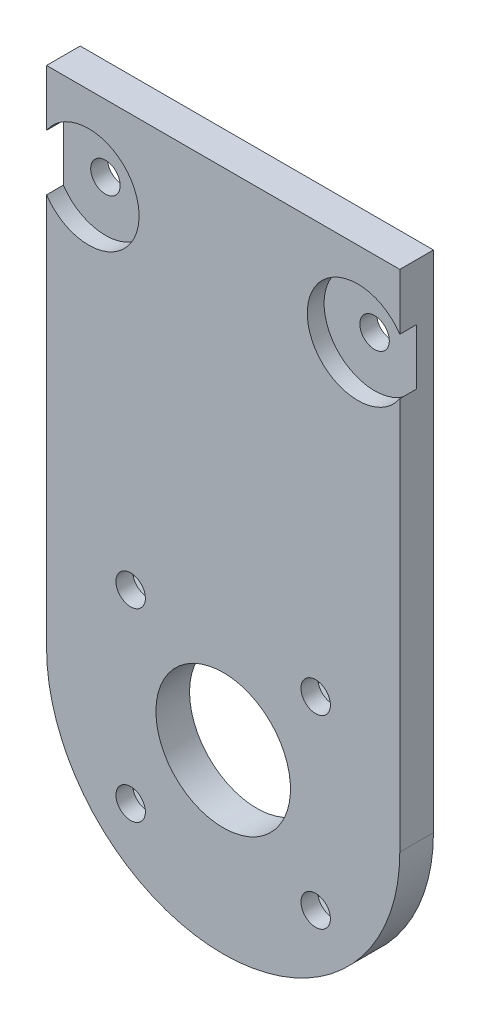
SolidWorks part; units mm, degrees
ref_plane "Front Plane" through (0, 0, 0) normal (0, 0, 1) x (1, 0, 0)
ref_plane "Top Plane" through (0, 0, 0) normal (0, 1, 0) x (1, 0, 0)
ref_plane "Right Plane" through (0, 0, 0) normal (1, 0, 0) x (0, 0, -1)
sketch "Sketch1" plane through (0, 0, 0) normal (0, 0, 1) x (1, 0, 0)
  line L2 (-21, 0) -> (-21, 60)
  line L3 (-21, 60) -> (21, 60)
  line L4 (21, 0) -> (21, 60)
  arc A0 (-21, 0) -> (21, 0) centre (0, 0) ccw
  dimension "D1" = 42
  dimension "D2" = 60
extrude "Boss-Extrude1" add sketch "Sketch1" along normal blind 4
sketch "Sketch2" plane through (0, 0, 0) normal (0, 0, -1) x (-1, 0, 0)
  circle A0 centre (0, 0) radius 6
  dimension "D1" = 12
extrude "Cut-Extrude1" cut sketch "Sketch2" against normal through all
sketch "Sketch3" plane through (0, 0, 0) normal (0, 0, -1) x (-1, 0, 0)
  circle A1 centre (0, 0) radius 8
  dimension "D1" = 16
extrude "Cut-Extrude2" cut sketch "Sketch3" against normal blind 4
sketch "Sketch4" plane through (0, 0, 0) normal (0, 0, -1) x (-1, 0, 0)
  line L0 (0, 3.306) -> (0, 0) construction
  line L1 (0, 0) -> (-2.3752, 0) construction
  circle A0 centre (-11, -11) radius 1.75
  circle A1 centre (-11, 11) radius 1.75
  circle A2 centre (11, 11) radius 1.75
  circle A3 centre (11, -11) radius 1.75
  dimension "D2" = 3.5
  dimension "D1" = 11
  dimension "D3" = 11
extrude "Cut-Extrude3" cut sketch "Sketch4" against normal through all
sketch "Sketch5" plane through (0, 0, 0) normal (0, 0, -1) x (-1, 0, 0)
  line L0 (0, -2.3059) -> (0, 0) construction
  line L1 (-11, -7.7091) -> (-13.85, -9.3546)
  line L2 (-13.85, -9.3546) -> (-13.85, -12.6454)
  line L3 (-13.85, -12.6454) -> (-11, -14.2909)
  line L4 (-11, -14.2909) -> (-8.15, -12.6454)
  line L5 (-8.15, -12.6454) -> (-8.15, -9.3546)
  line L6 (-8.15, -9.3546) -> (-11, -7.7091)
  line L7 (0, 0) -> (-2.4109, 0) construction
  line L8 (-8.15, 9.3546) -> (-11, 7.7091)
  line L9 (-8.15, 12.6454) -> (-8.15, 9.3546)
  line L10 (-11, 14.2909) -> (-8.15, 12.6454)
  line L11 (-13.85, 12.6454) -> (-11, 14.2909)
  line L12 (-13.85, 9.3546) -> (-13.85, 12.6454)
  line L13 (-11, 7.7091) -> (-13.85, 9.3546)
  line L14 (11, 7.7091) -> (13.85, 9.3546)
  line L15 (13.85, 9.3546) -> (13.85, 12.6454)
  line L16 (13.85, 12.6454) -> (11, 14.2909)
  line L17 (11, 14.2909) -> (8.15, 12.6454)
  line L18 (8.15, 12.6454) -> (8.15, 9.3546)
  line L19 (8.15, 9.3546) -> (11, 7.7091)
  line L20 (8.15, -9.3546) -> (11, -7.7091)
  line L21 (8.15, -12.6454) -> (8.15, -9.3546)
  line L22 (11, -14.2909) -> (8.15, -12.6454)
  line L23 (13.85, -12.6454) -> (11, -14.2909)
  line L24 (13.85, -9.3546) -> (13.85, -12.6454)
  line L25 (11, -7.7091) -> (13.85, -9.3546)
  circle A0 centre (-11, -11) radius 2.85 construction
  circle A1 centre (-11, 11) radius 2.85 construction
  circle A2 centre (11, 11) radius 2.85 construction
  circle A3 centre (11, -11) radius 2.85 construction
  dimension "D1" = 5.7
extrude "Cut-Extrude4" cut sketch "Sketch5" against normal blind 2
sketch "Sketch6" plane through (0, 0, 0) normal (0, 0, -1) x (-1, 0, 0)
  line L0 (0, 26.5885) -> (0, 14.8673) construction
  line L1 (-21, 60) -> (21, 60) construction
  line L2 (-21, 0) -> (-21, 60) construction
  circle A0 centre (-16, 50) radius 1.75
  circle A1 centre (16, 50) radius 1.75
  dimension "D1" = 3.5
  dimension "D2" = 10
  dimension "D3" = 5
extrude "Cut-Extrude5" cut sketch "Sketch6" against normal through all
sketch "Sketch7" plane through (0, 0, 4) normal (0, 0, 1) x (1, 0, 0)
  line L0 (0, 19.5559) -> (0, 31.5134) construction
  circle A0 centre (-16, 50) radius 6
  circle A1 centre (16, 50) radius 6
  dimension "D1" = 12
extrude "Cut-Extrude6" cut sketch "Sketch7" against normal blind 2
